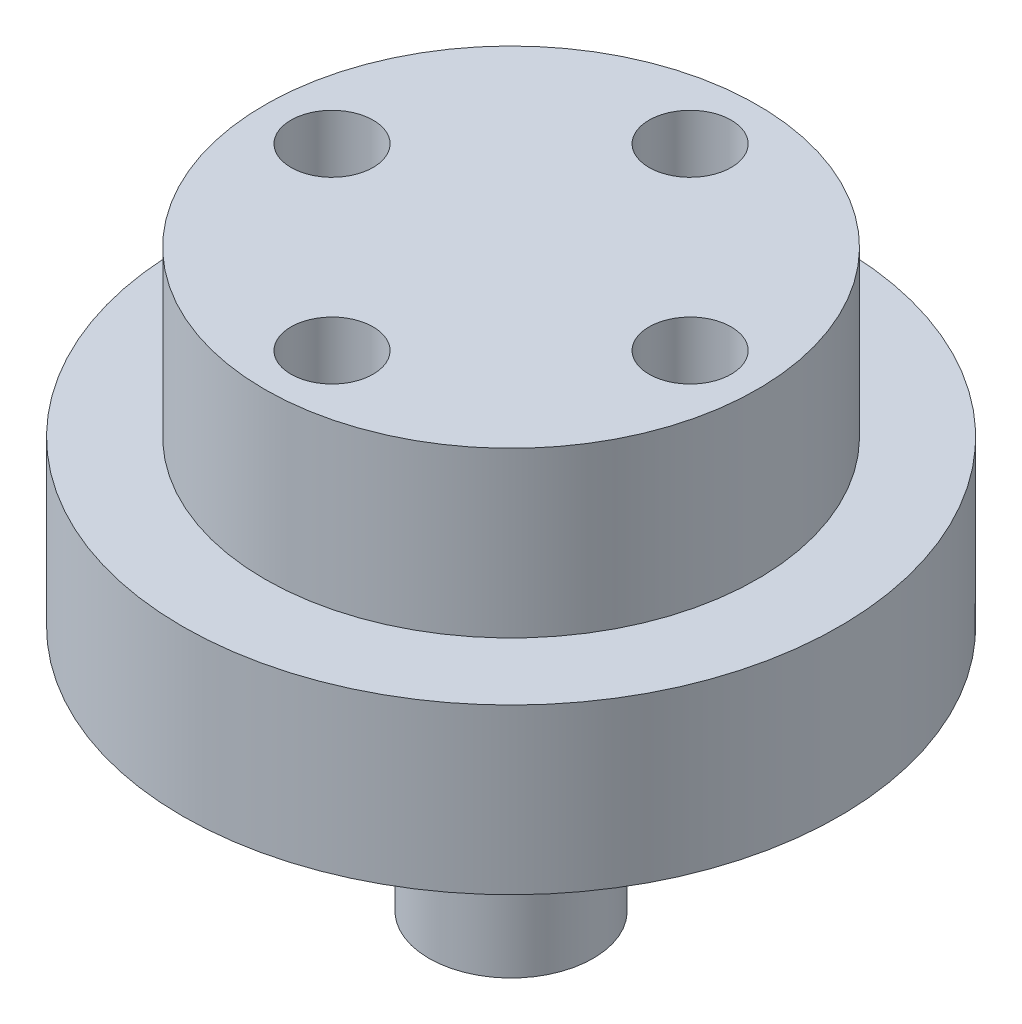
SolidWorks part; units mm, degrees
material "1060 Alloy"
ref_plane "Front Plane" through (0, 0, 0) normal (0, 0, 1) x (1, 0, 0)
ref_plane "Top Plane" through (0, 0, 0) normal (0, 1, 0) x (1, 0, 0)
ref_plane "Right Plane" through (0, 0, 0) normal (1, 0, 0) x (0, 0, -1)
sketch "Sketch1" plane through (0, 0, 0) normal (0, 1, 0) x (1, 0, 0)
  circle A0 centre (0, 0) radius 101.6
  dimension "D1" = 203.2
extrude "Boss-Extrude1" add sketch "Sketch1" along normal blind 50.8
sketch "Sketch2" plane through (0, 50.8, 0) normal (0, 1, 0) x (1, 0, 0)
  circle A0 centre (0, 0) radius 76.2
  dimension "D1" = 152.4
extrude "Boss-Extrude2" add sketch "Sketch2" along normal blind 50.8
sketch "Sketch3" plane through (0, 101.6, 0) normal (0, 1, 0) x (1, 0, 0)
  circle A0 centre (0, 0) radius 55.372 construction
  circle A1 centre (0, 55.372) radius 12.7
  circle A2 centre (-55.372, 0) radius 12.7
  circle A3 centre (0, -55.372) radius 12.7
  circle A4 centre (55.372, 0) radius 12.7
  dimension "D1" = 110.744
  dimension "D2" = 25.4
extrude "Cut-Extrude1" cut sketch "Sketch3" against normal through all
sketch "Sketch4" plane through (0, 0, 0) normal (0, -1, 0) x (1, 0, 0)
  circle A0 centre (0, 0) radius 25.4
  dimension "D1" = 50.8
extrude "Boss-Extrude3" add sketch "Sketch4" along normal blind 76.2
